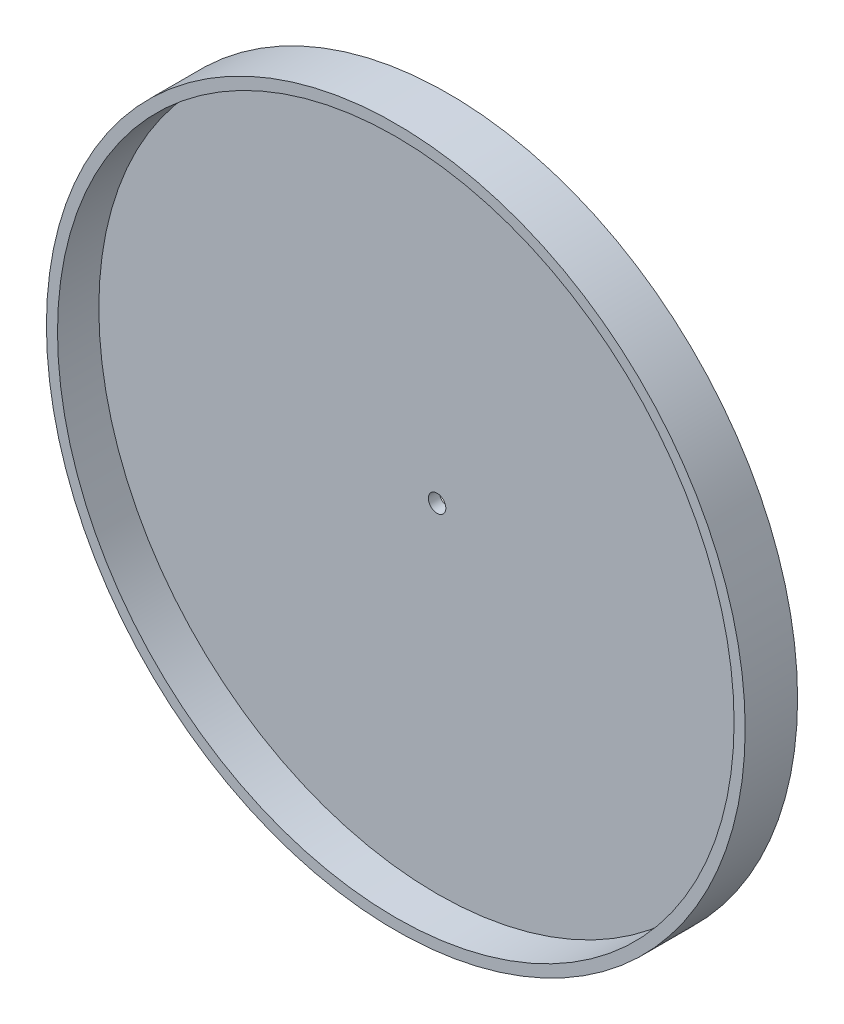
SolidWorks part; units mm, degrees
ref_plane "Front Plane" through (0, 0, 0) normal (0, 0, 1) x (1, 0, 0)
ref_plane "Top Plane" through (0, 0, 0) normal (0, 1, 0) x (1, 0, 0)
ref_plane "Right Plane" through (0, 0, 0) normal (1, 0, 0) x (0, 0, -1)
sketch "Sketch1" plane through (0, 0, 0) normal (0, 0, 1) x (1, 0, 0)
  circle A0 centre (0, 0) radius 100
  circle A1 centre (0, 0) radius 2.5
  dimension "D1" = 200
  dimension "D2" = 5
extrude "Boss-Extrude1" add sketch "Sketch1" along normal mid plane 15 contours A0 A1
sketch "Sketch2" plane through (0, 0, 7.5) normal (0, 0, 1) x (1, 0, 0)
  circle A0 centre (0, 0) radius 96.825
  circle A1 centre (0, 0) radius 100 construction
  dimension "D1" = 3.175
extrude "Cut-Extrude1" cut sketch "Sketch2" against normal offset from surface (11.825 mm away) 3.175 up to face at (2.5, 0, -7.5)
